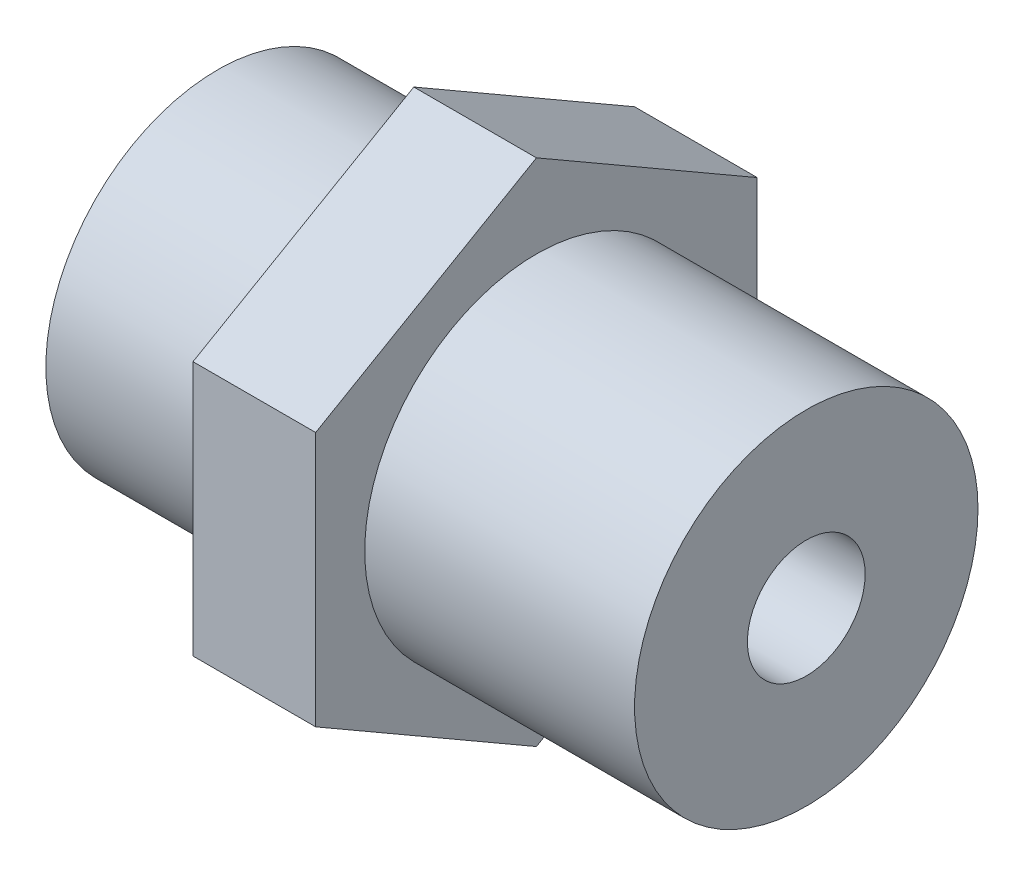
SolidWorks part; units mm, degrees
ref_plane "Alzado" through (0, 0, 0) normal (0, 0, 1) x (1, 0, 0)
ref_plane "Planta" through (0, 0, 0) normal (0, 1, 0) x (1, 0, 0)
ref_plane "Vista lateral" through (0, 0, 0) normal (1, 0, 0) x (0, 0, -1)
ref_plane "Plano2" through (-32, 0, 0) normal (1, 0, 0) x (0, 0, -1)
sketch "Sk_barril" plane through (-32, 0, 0) normal (1, 0, 0) x (0, 0, -1)
  circle A0 centre (-60.4, -16) radius 3.5
  circle A1 centre (-60.4, -16) radius 1.2
extrude "Barril" add sketch "Sk_barril" against normal blind 12
ref_plane "Plano4" through (-40, 0, 0) normal (1, 0, 0) x (0, 0, -1)
sketch "Sk_contratuerca" plane through (-40, 0, 0) normal (1, 0, 0) x (0, 0, -1)
  line L0 (-60.4, -10.8038) -> (-64.9, -13.4019)
  line L1 (-64.9, -13.4019) -> (-64.9, -18.5981)
  line L2 (-64.9, -18.5981) -> (-60.4, -21.1962)
  line L3 (-60.4, -21.1962) -> (-55.9, -18.5981)
  line L4 (-55.9, -18.5981) -> (-55.9, -13.4019)
  line L5 (-55.9, -13.4019) -> (-60.4, -10.8038)
  circle A0 centre (-60.4, -16) radius 1.2
extrude "Contratuerca" add sketch "Sk_contratuerca" along normal blind 2.5
